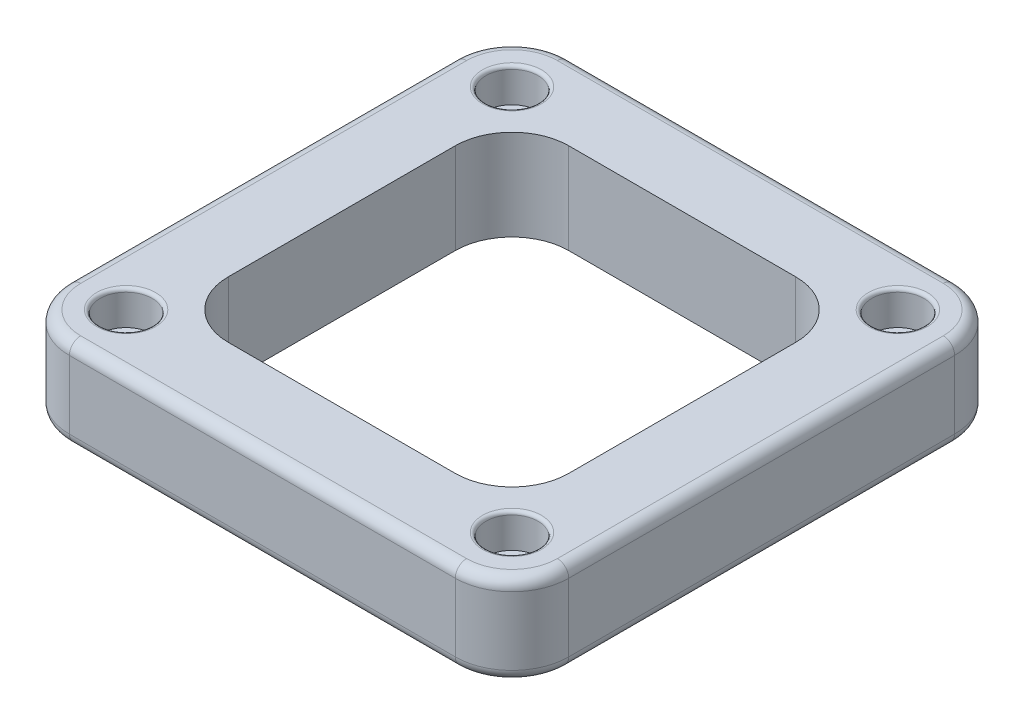
SolidWorks part; units mm, degrees
ref_plane "前视基准面" through (0, 0, 0) normal (0, 0, 1) x (1, 0, 0)
ref_plane "上视基准面" through (0, 0, 0) normal (0, 1, 0) x (1, 0, 0)
ref_plane "右视基准面" through (0, 0, 0) normal (1, 0, 0) x (0, 0, -1)
other "Configuration Table"
sketch "草图1" plane through (0, 0, 0) normal (0, 1, 0) x (1, 0, 0)
  line L0 (0, -55) -> (0, 55) construction
  line L1 (-22, 22) -> (22, 22)
  line L2 (-22, 22) -> (-22, -22)
  line L3 (-22, -22) -> (22, -22)
  line L4 (22, 22) -> (22, -22)
  line L5 (-55, 0) -> (55, 0) construction
  dimension "D1" = 44
  dimension "D2" = 44
  dimension "D3" = 22
  dimension "D4" = 22
extrude "凸台-拉伸1" add sketch "草图1" along normal blind 8
sketch "草图4" plane through (0, 8, 0) normal (0, 1, 0) x (1, 0, 0)
  point P0 (-17, 17)
  point P13 (-17, 17)
  dimension "D1" = 17
  dimension "D2" = 17
hole_wizard "CBORE for M2 Hex Head Machine Screw1" positions "草图4" profile "草图5" counterbore size "M2" standard "ANSI Metric" end condition up to next
sketch "草图5" plane through (-17, 8, -17) normal (1, 0, 0) x (0, 0, 1)
  line L0 (0, 0) -> (0, 8)
  line L1 (0, 8) -> (1.1, 8)
  line L3 (1.1, 8) -> (1.1, 3)
  line L4 (1.1, 3) -> (2.3, 3)
  line L5 (2.3, 3) -> (2.3, 0)
  line L7 (2.3, 0) -> (0, 0)
  line L11 (0, -6.35) -> (0, 107.95) construction
  dimension "Thru Hole Dia." = 2.2
  dimension "Thru Hole Depth" = 8
  dimension "C'Bore Dia." = 4.6
  dimension "C'Bore Depth" = 3
mirror "镜向1" about plane through (0, 0, 0) normal (0, 0, 1) of "CBORE for M2 Hex Head Machine Screw1" second plane through (0, 0, 0) second plane normal (1, 0, 0)
fillet "圆角2" radius 5 1 edges at (-22, 4, -22)
fillet "圆角3" radius 5 1 edges at (22, 4, -22)
fillet "圆角4" radius 5 1 edges at (22, 4, 22)
fillet "圆角5" radius 5 1 edges at (-22, 4, 22)
fillet "圆角6" radius 1 16 edges at (20.5355, 0, -20.5355) (22, 0, 0) (0, 0, -22) (-20.5355, 0, -20.5355) (-22, 0, 0) (-20.5355, 0, 20.5355) (20.5355, 0, 20.5355) (0, 0, 22) (20.5355, 8, 20.5355) (22, 8, 0) (20.5355, 8, -20.5355) (-20.5355, 8, -20.5355) (0, 8, -22) (-22, 8, 0) (-20.5355, 8, 20.5355) (0, 8, 22)
fillet "圆角7" radius 0.3 4 edges at (-17, 8, -14.7) (17, 8, -14.7) (-17, 8, 19.3) (17, 8, 19.3)
sketch "草图7" plane through (0, 8, 0) normal (0, 1, 0) x (1, 0, 0)
  line L7 (-15, 15) -> (15, 15)
  line L8 (-15, 15) -> (-15, -15)
  line L9 (-15, -15) -> (15, -15)
  line L10 (15, 15) -> (15, -15)
  dimension "D1" = 30
  dimension "D2" = 30
  dimension "D3" = 15
  dimension "D4" = 15
extrude "切除-拉伸2" cut sketch "草图7" against normal through all
fillet "圆角8" radius 5 1 edges at (-15, 4, -15)
fillet "圆角9" radius 5 1 edges at (15, 4, -15)
fillet "圆角10" radius 5 1 edges at (15, 4, 15)
fillet "圆角11" radius 5 1 edges at (-15, 4, 15)
